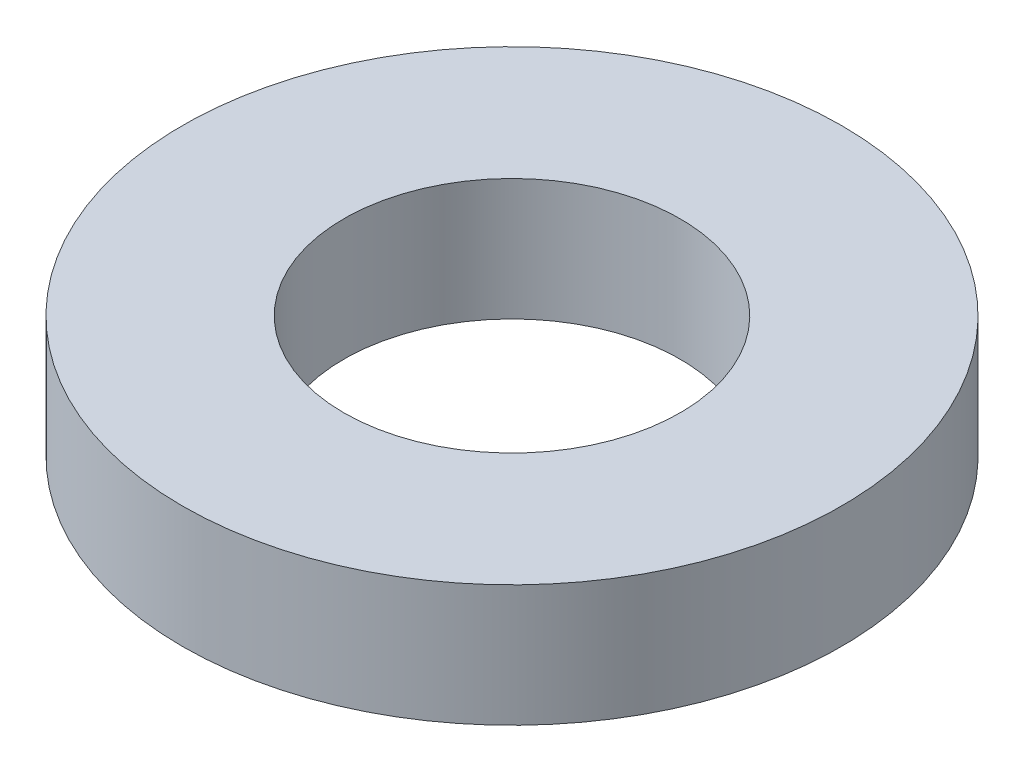
SolidWorks part; units mm, degrees
ref_plane "Front Plane" through (0, 0, 0) normal (0, 0, 1) x (1, 0, 0)
ref_plane "Top Plane" through (0, 0, 0) normal (0, 1, 0) x (1, 0, 0)
ref_plane "Right Plane" through (0, 0, 0) normal (1, 0, 0) x (0, 0, -1)
sketch "Sketch1" plane through (0, 0, 0) normal (0, 1, 0) x (1, 0, 0)
  circle A0 centre (0, 0) radius 7.9375
  dimension "D1" = 15.875
extrude "Boss-Extrude1" add sketch "Sketch1" along normal blind 2.93
sketch "Sketch2" plane through (0, 2.93, 0) normal (0, 1, 0) x (1, 0, 0)
  circle A0 centre (0, 0) radius 4
  dimension "D1" = 8
sketch "Sketch3" plane through (0, 2.93, 0) normal (0, 1, 0) x (1, 0, 0)
  circle A0 centre (0, 0) radius 4.05
  dimension "D1" = 8.1
extrude "Cut-Extrude2" cut sketch "Sketch3" against normal through all
